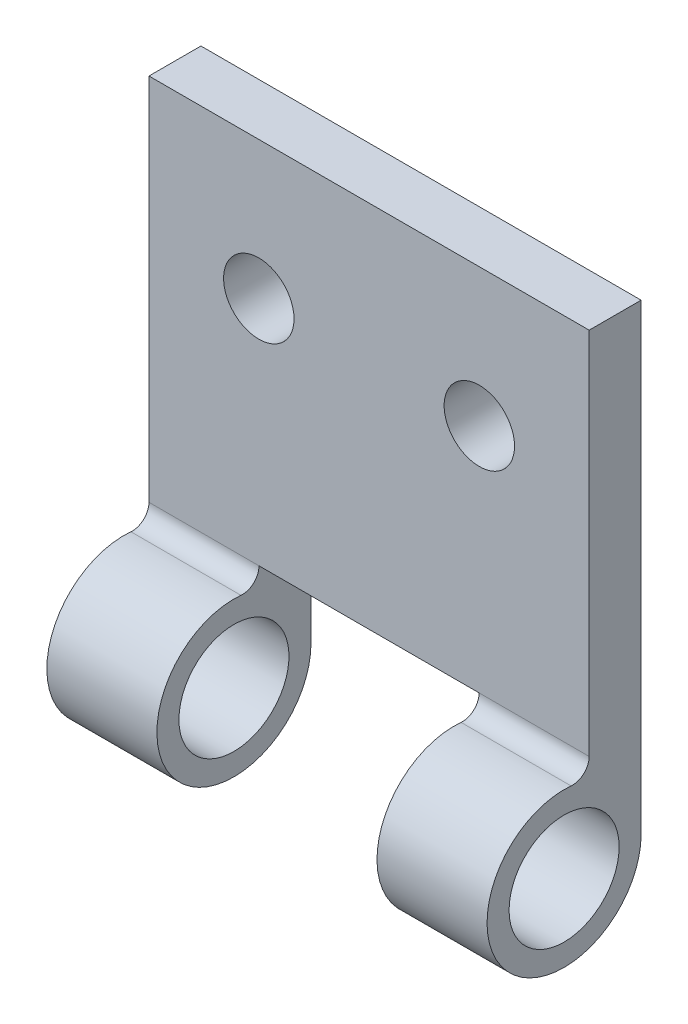
SolidWorks part; units mm, degrees
ref_plane "Front Plane" through (0, 0, 0) normal (0, 0, 1) x (1, 0, 0)
ref_plane "Top Plane" through (0, 0, 0) normal (0, 1, 0) x (1, 0, 0)
ref_plane "Right Plane" through (0, 0, 0) normal (1, 0, 0) x (0, 0, -1)
sketch "Sketch2" plane through (0, 0, 0) normal (1, 0, 0) x (0, 0, -1)
  line L0 (0.7234, 2.6893) -> (0.7234, 13.3401)
  line L1 (2.2225, 0) -> (2.2225, 13.3401)
  line L2 (2.2225, 13.3401) -> (0.7234, 13.3401)
  circle A0 centre (0, 0) radius 1.5875
  arc A1 (0.202, 2.2133) -> (2.2225, 0) centre (0, 0) ccw
  arc A2 (0.7234, 2.6893) -> (0.202, 2.2133) centre (0.2455, 2.6893) cw
  dimension "D2" = 3.175
  dimension "D3" = 2.2225
extrude "Boss-Extrude1" add sketch "Sketch2" along normal blind 12.7
sketch "Sketch3" plane through (0, 0, -0.7234) normal (0, 0, 1) x (1, 0, 0)
  line L3 (6.35, 13.3401) -> (6.35, 8.424)
  line L4 (12.7, 13.3401) -> (0, 13.3401) construction
  line L5 (3.1689, 9.3641) -> (6.35, 9.3641)
  line L6 (6.35, 9.3641) -> (9.5311, 9.3641)
  circle A0 centre (3.1689, 9.3641) radius 1.016
  circle A1 centre (9.5311, 9.3641) radius 1.016
extrude "Cut-Extrude1" cut sketch "Sketch3" against normal blind 12.7 contours A0 | A1
sketch "Sketch4" plane through (0, 0, -0.7234) normal (0, 0, 1) x (1, 0, 0)
  line L0 (6.35, 2.6893) -> (6.35, -2.2225)
  line L1 (12.7, 2.6893) -> (0, 2.6893) construction
  line L2 (0, -2.2225) -> (12.7, -2.2225) construction
  line L4 (3.175, -2.2225) -> (9.525, -2.2225)
  line L5 (3.175, -2.2225) -> (3.175, 2.6893)
  line L6 (3.175, 2.6893) -> (9.525, 2.6893)
  line L7 (9.525, -2.2225) -> (9.525, 2.6893)
  line L8 (3.175, -2.2225) -> (9.525, 2.6893) construction
  line L9 (3.175, 2.6893) -> (9.525, -2.2225) construction
  point P6 (6.35, 0.2334)
  dimension "D1" = 6.35
extrude "Cut-Extrude3" cut sketch "Sketch4" against normal blind 50.8 and the other way blind 5.08 contours L5 L6 L7 L4
scale "Scale1" scale about centroid uniform scaling yes scale factor 3
